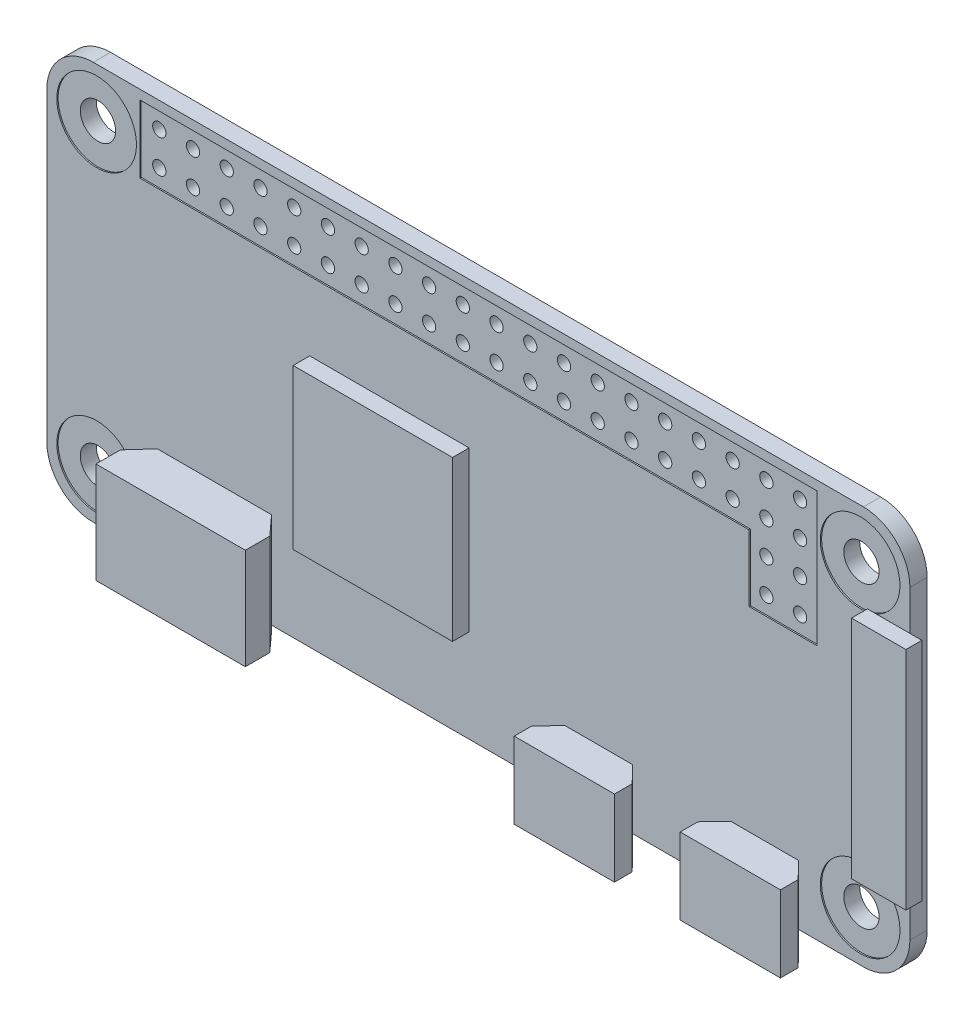
SolidWorks part; units mm, degrees
ref_plane "Front Plane" through (0, 0, 0) normal (0, 0, 1) x (1, 0, 0)
ref_plane "Top Plane" through (0, 0, 0) normal (0, 1, 0) x (1, 0, 0)
ref_plane "Right Plane" through (0, 0, 0) normal (1, 0, 0) x (0, 0, -1)
sketch "Sketch1" plane through (0, 0, 0) normal (0, 0, 1) x (1, 0, 0)
  line L1 (-29, -15) -> (29, -15)
  line L2 (-32.5, -11.5) -> (-32.5, 11.5)
  line L3 (-29, 15) -> (29, 15)
  line L4 (32.5, -11.5) -> (32.5, 11.5)
  line L5 (-32.5, -15) -> (32.5, 15) construction
  line L6 (-32.5, 15) -> (32.5, -15) construction
  arc A0 (-29, -15) -> (-32.5, -11.5) centre (-29, -11.5) cw
  arc A1 (29, -15) -> (32.5, -11.5) centre (29, -11.5) ccw
  arc A2 (29, 15) -> (32.5, 11.5) centre (29, 11.5) cw
  arc A3 (-32.5, 11.5) -> (-29, 15) centre (-29, 11.5) cw
  point P0 (0, 0)
  dimension "D3" = 3.5
  dimension "D1" = 65
  dimension "D2" = 30
extrude "Boss-Extrude1" add sketch "Sketch1" along normal blind 1.3
sketch "Sketch2" plane through (0, 0, 1.3) normal (0, 0, 1) x (1, 0, 0)
  line L0 (-32.5, 11.5) -> (-32.5, -11.5) construction
  line L1 (29, 15) -> (-29, 15) construction
  circle A0 centre (-28.75, 11.25) radius 1.33
  dimension "D1" = 2.66
  dimension "D2" = 3.75
  dimension "D3" = 3.75
extrude "Cut-Extrude1" cut sketch "Sketch2" against normal through all
mirror "Mirror1" about plane through (0, 0, 0) normal (0, 1, 0) of "Cut-Extrude1"
mirror "Mirror2" about plane through (0, 0, 0) normal (1, 0, 0) of "Mirror1", "Cut-Extrude1"
sketch "Sketch3" plane through (0, 0, 1.3) normal (0, 0, 1) x (1, 0, 0)
  line L0 (-25.5, 14.3) -> (25.5, 14.3)
  line L1 (29, 15) -> (-29, 15) construction
  line L2 (-25.5, 14.3) -> (-25.5, 9.2)
  line L3 (-25.5, 9.2) -> (20.4, 9.2)
  line L5 (-32.5, 11.5) -> (-32.5, -11.5) construction
  line L6 (25.5, 14.3) -> (25.5, 4.2)
  line L7 (25.5, 4.2) -> (20.4, 4.2)
  line L8 (20.4, 9.2) -> (20.4, 4.2)
  dimension "D1" = 51
  dimension "D2" = 5.1
  dimension "D3" = 5.1
  dimension "D4" = 0.7
  dimension "D5" = 7
  dimension "D6" = 5
extrude "Cut-Extrude2" cut sketch "Sketch3" against normal blind 0.1
sketch "Sketch4" plane through (0, 0, 1.2) normal (0, 0, 1) x (1, 0, 0)
  line L0 (29, 15) -> (-29, 15) construction
  line L1 (-32.5, 11.5) -> (-32.5, -11.5) construction
  circle A0 centre (-24.13, 13) radius 0.5
  dimension "D1" = 1
  dimension "D2" = 2
  dimension "D3" = 8.37
extrude "Cut-Extrude3" cut sketch "Sketch4" against normal through all
pattern_linear "LPattern1" count 20 spacing 2.54 along (1, 0, 0) count 2 spacing 2.5 along (0, -1, 0) of "Cut-Extrude3"
sketch "Sketch5" plane through (0, 0, 1.2) normal (0, 0, 1) x (1, 0, 0)
  circle A0 centre (21.59, 8) radius 0.5
  point P2 (0, 0)
  dimension "D1" = 1
  dimension "D2" = 2.5
extrude "Cut-Extrude4" cut sketch "Sketch5" against normal through all
pattern_linear "LPattern2" count 2 spacing 2.54 along (1, 0, 0) count 2 spacing 2.5 along (0, -1, 0) of "Cut-Extrude4"
sketch "Sketch7" plane through (0, 0, 1.3) normal (0, 0, 1) x (1, 0, 0)
  circle A0 centre (-28.75, 11.25) radius 3
  dimension "D1" = 6
extrude "Cut-Extrude5" cut sketch "Sketch7" against normal blind 0.1
mirror "Mirror3" about plane through (0, 0, 0) normal (0, 1, 0) of "Cut-Extrude5"
mirror "Mirror4" about plane through (0, 0, 0) normal (1, 0, 0) of "Mirror3", "Cut-Extrude5"
sketch "Sketch8" plane through (0, 0, 1.3) normal (0, 0, 1) x (1, 0, 0)
  line L0 (-29, -15) -> (29, -15) construction
  line L1 (-12.7, -8) -> (-0.7, -8)
  line L2 (-12.7, -8) -> (-12.7, 4)
  line L3 (-12.7, 4) -> (-0.7, 4)
  line L4 (-0.7, -8) -> (-0.7, 4)
  line L5 (-32.5, 11.5) -> (-32.5, -11.5) construction
  dimension "D1" = 12
  dimension "D2" = 12
  dimension "D3" = 7
  dimension "D4" = 19.8
extrude "Boss-Extrude2" add sketch "Sketch8" along normal blind 1.25
sketch "Sketch9" plane through (0, 0, 0) normal (0, 1, 0) x (1, 0, 0)
  line L1 (-24.175, -1.3) -> (-15.575, -1.3)
  line L2 (-25.5, -2.76) -> (-25.5, -4.6)
  line L3 (-25.5, -4.6) -> (-14.25, -4.6)
  line L4 (-14.25, -2.76) -> (-14.25, -4.6)
  line L5 (-32.5, -1.3) -> (-32.5, 0) construction
  line L6 (-25.5, -2.76) -> (-24.175, -1.3)
  line L7 (-15.575, -1.3) -> (-14.25, -2.76)
  line L8 (-29, -1.3) -> (29, -1.3) construction
  point P0 (0, 0)
  dimension "D1" = 11.25
  dimension "D2" = 1.84
  dimension "D3" = 7
  dimension "D4" = 8.6
  dimension "D5" = 3.3
extrude "Boss-Extrude3" add sketch "Sketch9" against normal blind 7.6 from offset 7.8 offset against normal yes
sketch "Sketch10" plane through (0, -15.4, 0) normal (0, -1, 0) x (1, 0, 0)
  line L12 (-14.6, 2.8951) -> (-14.6, 4.25)
  line L13 (-14.6, 4.25) -> (-25.15, 4.25)
  line L14 (-25.15, 4.25) -> (-25.15, 2.8951)
  line L15 (-25.15, 2.8951) -> (-24.02, 1.65)
  line L16 (-24.02, 1.65) -> (-15.73, 1.65)
  line L17 (-15.73, 1.65) -> (-14.6, 2.8951)
  line L18 (-14.6, 2.8951) -> (-14.6, 4.25)
  line L19 (-14.6, 4.25) -> (-25.15, 4.25)
  line L20 (-25.15, 4.25) -> (-25.15, 2.8951)
  line L21 (-25.15, 2.8951) -> (-24.02, 1.65)
  line L22 (-24.02, 1.65) -> (-15.73, 1.65)
  line L23 (-15.73, 1.65) -> (-14.6, 2.8951)
  dimension "D1" = 0.35
extrude "Cut-Extrude6" cut sketch "Sketch10" against normal blind 7.25
sketch "Sketch12" plane through (0, 0, 0) normal (0, 1, 0) x (1, 0, 0)
  line L0 (17.8, -3.9) -> (25.35, -3.9)
  line L1 (25.35, -3.9) -> (25.35, -2.57)
  line L2 (25.35, -2.57) -> (24.125, -1.3)
  line L3 (24.125, -1.3) -> (19.025, -1.3)
  line L4 (19.025, -1.3) -> (17.8, -2.57)
  line L5 (17.8, -2.57) -> (17.8, -3.9)
  line L6 (32.5, -1.3) -> (32.5, 0) construction
  line L7 (-15.575, -1.3) -> (29, -1.3) construction
  point P4 (21.575, -1.3)
  point P7 (21.575, -3.9)
  point P10 (32.5, -0.65)
  point P11 (0, 0)
  point P14 (0, 0)
  dimension "D1" = 7.55
  dimension "D2" = 2.6
  dimension "D3" = 1.33
  dimension "D4" = 5.1
  dimension "D5" = 7.15
extrude "Boss-Extrude4" add sketch "Sketch12" against normal blind 5.75 from offset 10.5 offset against normal yes
sketch "Sketch13" plane through (0, -16.25, 0) normal (0, -1, 0) x (1, 0, 0)
  line L12 (18.15, 3.55) -> (18.15, 2.7113)
  line L13 (18.15, 2.7113) -> (19.1737, 1.65)
  line L14 (19.1737, 1.65) -> (23.9763, 1.65)
  line L15 (23.9763, 1.65) -> (25, 2.7113)
  line L16 (25, 2.7113) -> (25, 3.55)
  line L17 (25, 3.55) -> (18.15, 3.55)
  line L18 (18.15, 3.55) -> (18.15, 2.7113)
  line L19 (18.15, 2.7113) -> (19.1737, 1.65)
  line L20 (19.1737, 1.65) -> (23.9763, 1.65)
  line L21 (23.9763, 1.65) -> (25, 2.7113)
  line L22 (25, 2.7113) -> (25, 3.55)
  line L23 (25, 3.55) -> (18.15, 3.55)
  dimension "D1" = 0.35
extrude "Cut-Extrude7" cut sketch "Sketch13" against normal blind 5.4
pattern_linear "LPattern3" count 2 spacing 12.5 along (-1, 0, 0) of "Cut-Extrude7", "Boss-Extrude4"
sketch "Sketch14" plane through (0, 0, 0) normal (1, 0, 0) x (0, 0, -1)
  line L0 (-1.3, -11.5) -> (-1.3, 11.5) construction
  line L1 (-1.3, 8.5) -> (-2.5, 8.5)
  line L2 (-1.3, 8.5) -> (-1.3, -8.5)
  line L3 (-1.3, -8.5) -> (-2.5, -8.5)
  line L4 (-2.5, 8.5) -> (-2.5, -8.5)
  point P6 (-2.5, 0)
  dimension "D1" = 17
  dimension "D2" = 1.2
extrude "Boss-Extrude5" add sketch "Sketch14" along normal blind 4.1 from offset 29.3
